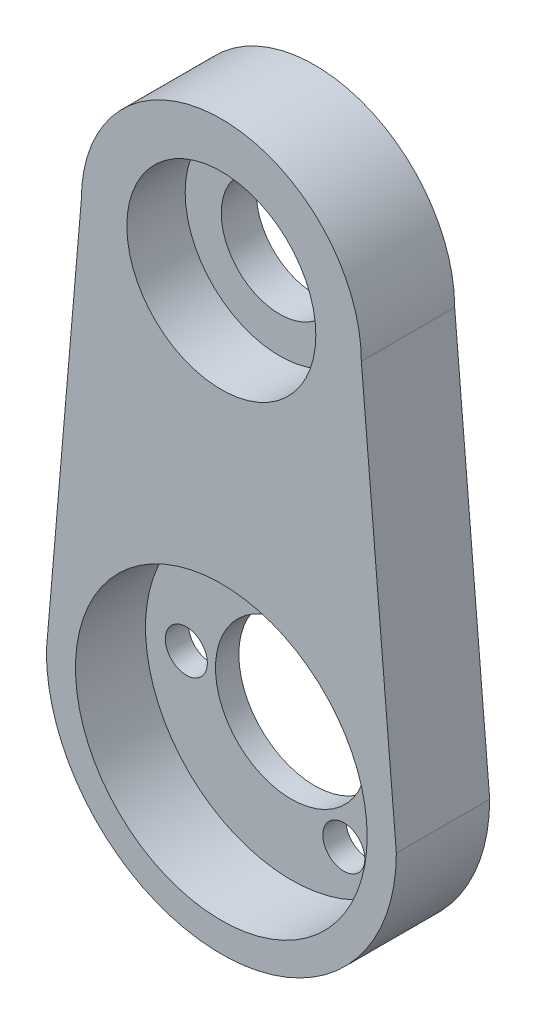
SolidWorks part; units mm, degrees
ref_plane "Plan de face" through (0, 0, 0) normal (0, 0, 1) x (1, 0, 0)
ref_plane "Plan de dessus" through (0, 0, 0) normal (0, 1, 0) x (1, 0, 0)
ref_plane "Plan de droite" through (0, 0, 0) normal (1, 0, 0) x (0, 0, -1)
sketch "Esquisse1" plane through (0, 0, 0) normal (0, 0, 1) x (1, 0, 0)
  line L0 (-16.3093, 0) -> (24.5372, 0) construction
  line L1 (12, 0) -> (15, -35)
  line L2 (-12, 0) -> (-15, -35)
  line L3 (-15, -35) -> (15, -35) construction
  line L4 (0, 0) -> (0, -35) construction
  arc A0 (-12, 0) -> (12, 0) centre (0, 0) cw
  arc A1 (-15, -35) -> (15, -35) centre (0, -35) ccw
  dimension "D1" = 12
  dimension "D2" = 15
  dimension "D3" = 35
extrude "Boss.-Extru.1" add sketch "Esquisse1" along normal blind 8
sketch "Esquisse2" plane through (0, 0, 8) normal (0, 0, 1) x (1, 0, 0)
  line L0 (0, 0) -> (0, -50) construction
  line L1 (15, -35) -> (-15, -35) construction
  circle A0 centre (0, -35) radius 6.5
  arc A1 (-15, -35) -> (15, -35) centre (0, -35) ccw construction
extrude "Enlèv. mat.-Extru.1" cut sketch "Esquisse2" against normal blind 10
sketch "Esquisse3" plane through (0, 0, 8) normal (0, 0, 1) x (1, 0, 0)
  line L0 (0, -35) -> (0, 0) construction
  line L1 (0, -35) -> (4.5, -27.2058) construction
  line L4 (0, -35) -> (-9, -35) construction
  line L5 (-9, -35) -> (0, -35) construction
  line L6 (0, -35) -> (4.5, -42.7942) construction
  circle A6 centre (4.5, -42.7942) radius 1.8
  circle A7 centre (-9, -35) radius 1.8
  circle A8 centre (4.5, -27.2058) radius 1.8
  dimension "D1" = 120
  dimension "D2" = 120
  dimension "D3" = 120
extrude "Enlèv. mat.-Extru.2" cut sketch "Esquisse3" against normal blind 10
ref_plane "Plan1" through (0, 10, 0) normal (0, 1, 0) x (1, 0, 0)
sketch "Esquisse5" plane through (0, 0, 8) normal (0, 0, 1) x (1, 0, 0)
  circle A0 centre (0, -35) radius 12.5
  dimension "D1" = 25
extrude "Enlèv. mat.-Extru.5" cut sketch "Esquisse5" against normal blind 6
sketch "Esquisse19" plane through (0, 0, 8) normal (0, 0, 1) x (1, 0, 0)
  circle A0 centre (0, 0) radius 8.1
extrude "Enlèv. mat.-Extru.6" cut sketch "Esquisse19" against normal blind 10 contours A0
sketch "Esquisse21" plane through (0, 0, 0) normal (0, 0, -1) x (-1, 0, 0)
  line L0 (-12, 0) -> (-15, -35)
  line L1 (12, 0) -> (15, -35)
  circle A0 centre (0, 0) radius 12
  circle A1 centre (0, -35) radius 15
sketch "Esquisse22" plane through (0, 0, 0) normal (0, 0, -1) x (-1, 0, 0)
  circle A0 centre (0, 0) radius 8.1
  circle A1 centre (0, 0) radius 5
extrude "Boss.-Extru.2" add sketch "Esquisse22" against normal blind 3
